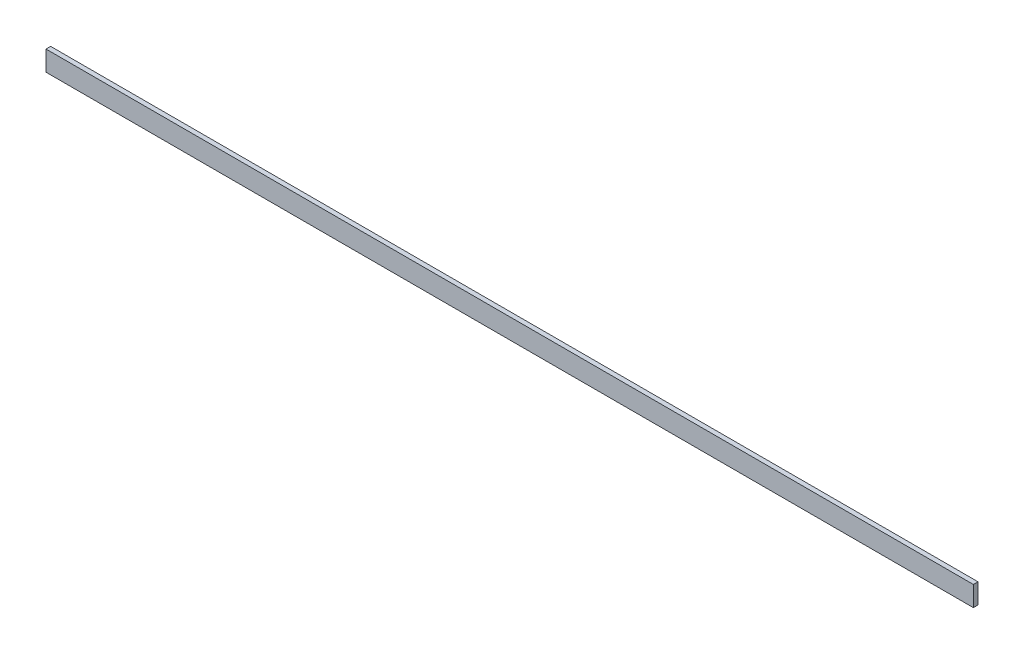
SolidWorks part; units mm, degrees
ref_plane "Front Plane" through (0, 0, 0) normal (0, 0, 1) x (1, 0, 0)
ref_plane "Top Plane" through (0, 0, 0) normal (0, 1, 0) x (1, 0, 0)
ref_plane "Right Plane" through (0, 0, 0) normal (1, 0, 0) x (0, 0, -1)
sketch "Sketch1" plane through (0, 0, 0) normal (0, 0, 1) x (1, 0, 0)
  line L1 (-300, 6.5) -> (300, 6.5)
  line L2 (-300, 6.5) -> (-300, -6.5)
  line L3 (-300, -6.5) -> (300, -6.5)
  line L4 (300, 6.5) -> (300, -6.5)
  line L5 (-300, 6.5) -> (300, -6.5) construction
  line L6 (-300, -6.5) -> (300, 6.5) construction
  point P0 (0, 0)
  dimension "D1" = 600
  dimension "D2" = 13
extrude "Boss-Extrude1" add sketch "Sketch1" along normal blind 3
